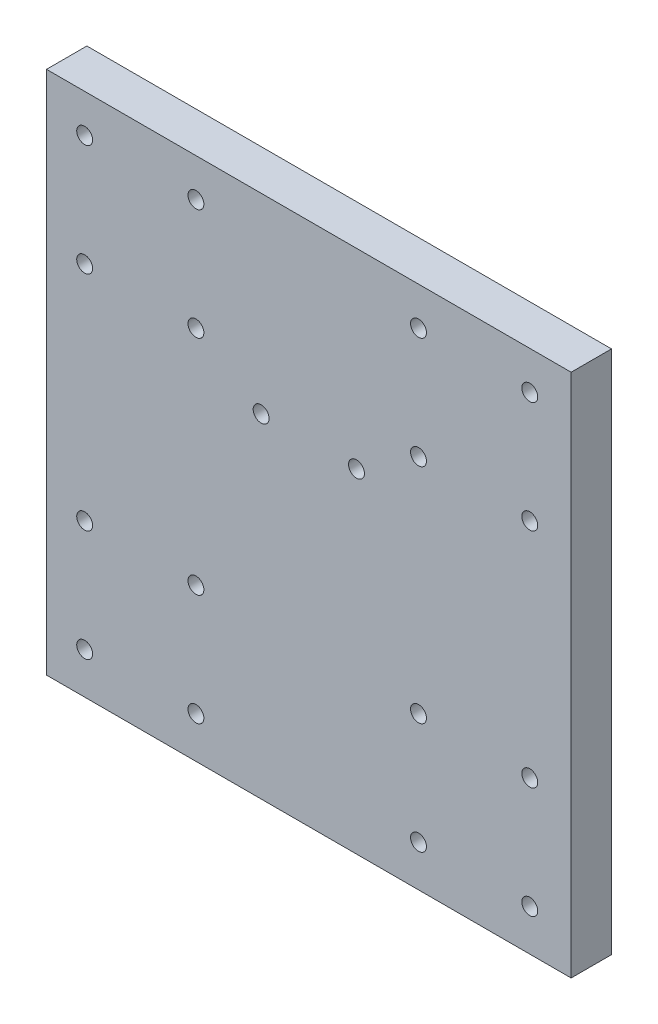
SolidWorks part; units mm, degrees
material "Aleación 1060"
ref_plane "Alzado" through (0, 0, 0) normal (0, 0, 1) x (1, 0, 0)
ref_plane "Planta" through (0, 0, 0) normal (0, 1, 0) x (1, 0, 0)
ref_plane "Vista lateral" through (0, 0, 0) normal (1, 0, 0) x (0, 0, -1)
sketch "Croquis1" plane through (0, 0, 0) normal (0, 0, 1) x (1, 0, 0)
  line L1 (82.5, -82.5) -> (-82.5, -82.5)
  line L2 (82.5, -82.5) -> (82.5, 82.5)
  line L3 (82.5, 82.5) -> (-82.5, 82.5)
  line L4 (-82.5, -82.5) -> (-82.5, 82.5)
  line L5 (82.5, -82.5) -> (-82.5, 82.5) construction
  line L6 (82.5, 82.5) -> (-82.5, -82.5) construction
  circle A0 centre (-70.5, 70.5) radius 2.5
  circle A1 centre (-35.5, 70.5) radius 2.5
  circle A2 centre (-35.5, 35.5) radius 2.5
  circle A3 centre (-70.5, 35.5) radius 2.5
  circle A4 centre (34.5, 70.5) radius 2.5
  circle A5 centre (69.5, 70.5) radius 2.5
  circle A6 centre (69.5, 35.5) radius 2.5
  circle A7 centre (34.5, 35.5) radius 2.5
  circle A8 centre (34.5, -34.5) radius 2.5
  circle A9 centre (69.5, -34.5) radius 2.5
  circle A10 centre (69.5, -69.5) radius 2.5
  circle A11 centre (34.5, -69.5) radius 2.5
  circle A12 centre (-70.5, -34.5) radius 2.5
  circle A13 centre (-35.5, -34.5) radius 2.5
  circle A14 centre (-35.5, -69.5) radius 2.5
  circle A15 centre (-70.5, -69.5) radius 2.5
  point P0 (0, 0)
  dimension "D3" = 5
  dimension "D1" = 165
  dimension "D2" = 165
  dimension "D4" = 12
  dimension "D5" = 12
  dimension "D6" = 2
  dimension "D7" = 2
  dimension "D8" = 2
  dimension "D9" = 2
extrude "Saliente-Extruir1" add sketch "Croquis1" along normal blind 12.7
sketch "Croquis2" plane through (0, 0, 12.7) normal (0, 0, 1) x (1, 0, 0)
  circle A0 centre (-15, 22.3901) radius 2.5
  circle A1 centre (15, 22.3901) radius 2.5
  circle A2 centre (69.5, -69.5) radius 2.5 construction
  circle A3 centre (69.5, -34.5) radius 2.5 construction
  circle A4 centre (34.5, -69.5) radius 2.5 construction
  circle A5 centre (34.5, -34.5) radius 2.5 construction
  circle A6 centre (-35.5, -69.5) radius 2.5 construction
  circle A7 centre (-70.5, -69.5) radius 2.5 construction
  circle A8 centre (-35.5, -34.5) radius 2.5 construction
  circle A9 centre (-70.5, -34.5) radius 2.5 construction
  circle A10 centre (69.5, 35.5) radius 2.5 construction
  circle A11 centre (34.5, 35.5) radius 2.5 construction
  circle A12 centre (69.5, 70.5) radius 2.5 construction
  circle A13 centre (34.5, 70.5) radius 2.5 construction
  circle A14 centre (-35.5, 35.5) radius 2.5 construction
  circle A15 centre (-70.5, 35.5) radius 2.5 construction
  circle A16 centre (-35.5, 70.5) radius 2.5 construction
  circle A17 centre (-70.5, 70.5) radius 2.5 construction
  circle A18 centre (69.5, -69.5) radius 2.5
  circle A19 centre (69.5, -34.5) radius 2.5
  circle A20 centre (34.5, -69.5) radius 2.5
  circle A21 centre (34.5, -34.5) radius 2.5
  circle A22 centre (-35.5, -69.5) radius 2.5
  circle A23 centre (-70.5, -69.5) radius 2.5
  circle A24 centre (-35.5, -34.5) radius 2.5
  circle A25 centre (-70.5, -34.5) radius 2.5
  circle A26 centre (69.5, 35.5) radius 2.5
  circle A27 centre (34.5, 35.5) radius 2.5
  circle A28 centre (69.5, 70.5) radius 2.5
  circle A29 centre (34.5, 70.5) radius 2.5
  circle A30 centre (-35.5, 35.5) radius 2.5
  circle A31 centre (-70.5, 35.5) radius 2.5
  circle A32 centre (-35.5, 70.5) radius 2.5
  circle A33 centre (-70.5, 70.5) radius 2.5
  dimension "D1" = 5
  dimension "D2" = 5
  dimension "D3" = 30
  dimension "D4" = 15
extrude "Cortar-Extruir1" cut sketch "Croquis2" against normal blind 12.7
